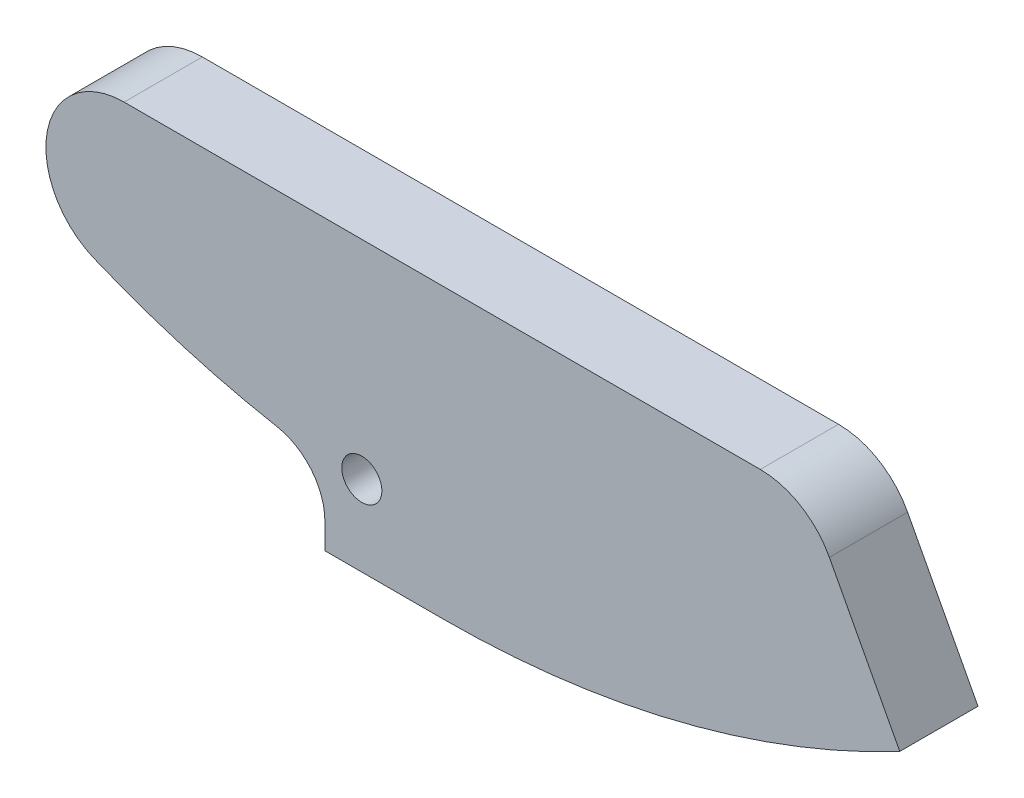
SolidWorks part; units mm, degrees
ref_plane "前视基准面" through (0, 0, 0) normal (0, 0, 1) x (1, 0, 0)
ref_plane "上视基准面" through (0, 0, 0) normal (0, 1, 0) x (1, 0, 0)
ref_plane "右视基准面" through (0, 0, 0) normal (1, 0, 0) x (0, 0, -1)
sketch "草图1" plane through (0, 0, 0) normal (0, 0, 1) x (1, 0, 0)
  line L5 (0, -50) -> (-6, -50)
  line L11 (23.3969, -44.1881) -> (19.7979, -37.3931)
  line L12 (-16.264, -35.2649) -> (16.264, -35.266)
  line L13 (-6, -46.1113) -> (-6, -50)
  arc A10 (16.264, -35.266) -> (19.7979, -37.3931) centre (16.264, -39.2649) cw
  arc A13 (0, -50) -> (23.3969, -44.1881) centre (0, 0) ccw
  arc A14 (-16.264, -35.2649) -> (-17.7948, -42.9604) centre (-16.264, -39.2649) ccw
  arc A16 (-17.7948, -42.9604) -> (-6, -46.1113) centre (0, 0) ccw
  point P12 (0, -32.5133)
extrude "凸台-拉伸1" add sketch "草图1" along normal blind 4
hole_wizard "M2.5x0.45 螺纹孔1" positions "3D草图1" profile "草图2" tap size "M2.5x0.45" standard "BSI" end condition through all
sketch3d "3D草图1"
  point P8 (-4.11, -45.89, 4)
  point P11 (-4.11, -45.89, 4)
sketch "草图2" plane through (-4.11, -45.89, 4) normal (1, 0, 0) x (0, -1, 0)
  line L0 (0, 0) -> (0, 4)
  line L1 (0, 4) -> (1.025, 4)
  line L2 (1.025, 4) -> (1.025, 0)
  line L5 (1.025, 0) -> (0, 0)
  line L11 (0, -6.35) -> (0, 107.95) construction
  dimension "通孔螺纹孔钻头直径" = 2.05
  dimension "通孔螺纹孔钻头深度" = 4
cosmetic thread "孔螺蚊线1" parameters "D2"=2.5
fillet "圆角1" radius 3 1 edges at (-6, -46.1113, 2)
